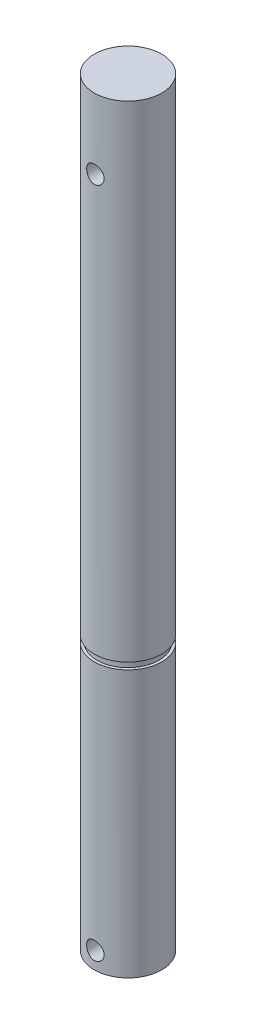
SolidWorks part; units mm, degrees
ref_plane "Front Plane" through (0, 0, 0) normal (0, 0, 1) x (1, 0, 0)
ref_plane "Top Plane" through (0, 0, 0) normal (0, 1, 0) x (1, 0, 0)
ref_plane "Right Plane" through (0, 0, 0) normal (1, 0, 0) x (0, 0, -1)
sketch "Sketch1" plane through (0, 0, 0) normal (0, 1, 0) x (1, 0, 0)
  circle A0 centre (0, 0) radius 3.175
extrude "Boss-Extrude1" add sketch "Sketch1" along normal mid plane 76.2
sketch "Sketch2" plane through (0, -38.1, 0) normal (0, -1, 0) x (1, 0, 0)
  circle A0 centre (0, 0.164) radius 7.2372
extrude "Cut-Extrude1" cut sketch "Sketch2" against normal blind 4.7625
sketch "Sketch4" plane through (0, 0, 0) normal (0, 0, 1) x (1, 0, 0)
  line L0 (0, -33.3375) -> (0, -31.7436) construction
  line L2 (0, -31.7436) -> (0, -30.1498) construction
  circle A0 centre (0, 31.4893) radius 0.8255
  circle A1 centre (0, -31.7436) radius 0.8255
extrude "Cut-Extrude2" cut sketch "Sketch4" against normal through all and the other way through all
sketch "Sketch5" plane through (0, -7.6073, 0) normal (0, -1, 0) x (1, 0, 0)
  circle A0 centre (0, 0) radius 3.175
  circle A1 centre (0, 0) radius 2.9167
extrude "Cut-Extrude3" cut sketch "Sketch5" along normal blind 0.635
